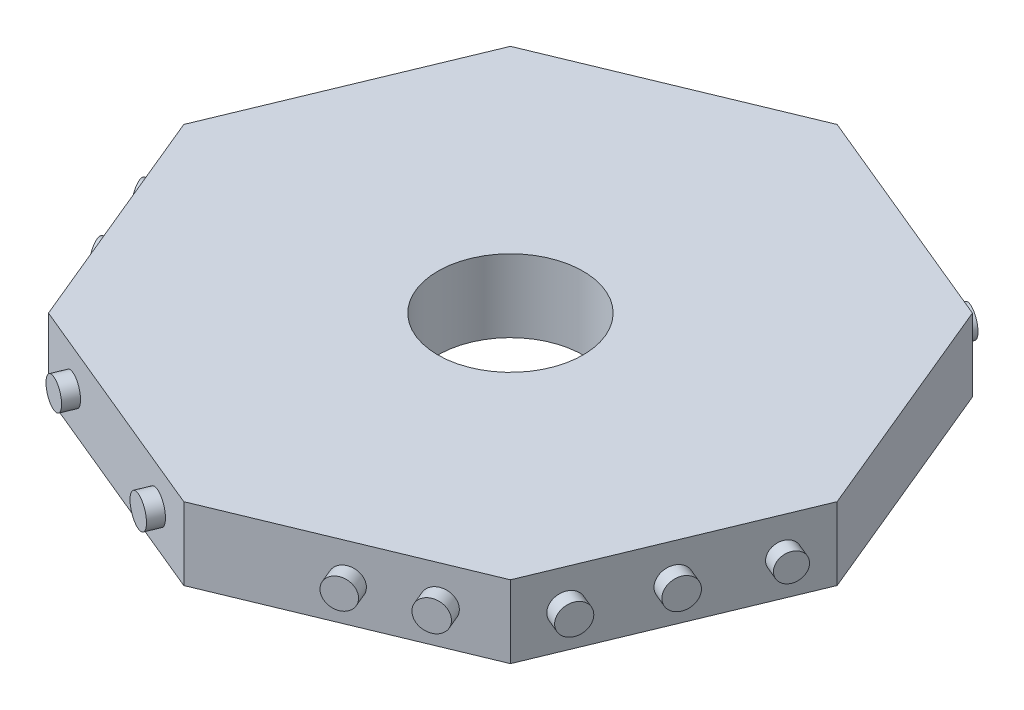
SolidWorks part; units mm, degrees
ref_plane "Front Plane" through (0, 0, 0) normal (0, 0, 1) x (1, 0, 0)
ref_plane "Top Plane" through (0, 0, 0) normal (0, 1, 0) x (1, 0, 0)
ref_plane "Right Plane" through (0, 0, 0) normal (1, 0, 0) x (0, 0, -1)
sketch "Sketch2" plane through (0, 0, 0) normal (0, 1, 0) x (1, 0, 0)
  line L1 (57.1139, 0) -> (40.3856, 40.3856)
  line L2 (40.3856, 40.3856) -> (0, 57.1139)
  line L3 (0, 57.1139) -> (-40.3856, 40.3856)
  line L4 (-40.3856, 40.3856) -> (-57.1139, 0)
  line L5 (-57.1139, 0) -> (-40.3856, -40.3856)
  line L6 (-40.3856, -40.3856) -> (0, -57.1139)
  line L7 (0, -57.1139) -> (40.3856, -40.3856)
  line L8 (40.3856, -40.3856) -> (57.1139, 0)
  circle A0 centre (0, 0) radius 52.7663 construction
extrude "Boss-Extrude1" add sketch "Sketch2" along normal blind 12.7
sketch "Sketch6" plane through (20.1928, 0, 48.7497) normal (0.3827, 0, 0.9239) x (0.9239, 0, -0.3827)
  circle A0 centre (0, 6.35) radius 2.5823
extrude "Boss-Extrude5" add sketch "Sketch6" along normal blind 2.54
sketch "Sketch8" plane through (20.1928, 0, 48.7497) normal (0.3827, 0, 0.9239) x (0.9239, 0, -0.3827)
  circle A0 centre (12.3695, 6.35) radius 2.6506
extrude "Boss-Extrude7" add sketch "Sketch8" along normal blind 2.54
sketch "Sketch9" plane through (-20.1928, 0, 48.7497) normal (-0.3827, 0, 0.9239) x (0.9239, 0, 0.3827)
  circle A0 centre (13.2827, 6.35) radius 2.6552
extrude "Boss-Extrude8" add sketch "Sketch9" along normal blind 2.54
sketch "Sketch10" plane through (-20.1928, 0, 48.7497) normal (-0.3827, 0, 0.9239) x (0.9239, 0, 0.3827)
  circle A0 centre (-14.0089, 6.35) radius 2.5136
extrude "Boss-Extrude9" add sketch "Sketch10" against normal blind 2.032 and the other way blind 2.54
sketch "Sketch11" plane through (-48.7497, 0, 20.1928) normal (-0.9239, 0, 0.3827) x (0.3827, 0, 0.9239)
  circle A0 centre (-13.6371, 6.35) radius 2.5862
extrude "Boss-Extrude10" add sketch "Sketch11" along normal blind 2.54
sketch "Sketch12" plane through (-48.7497, 0, 20.1928) normal (-0.9239, 0, 0.3827) x (0.3827, 0, 0.9239)
  circle A0 centre (0, 6.35) radius 2.6354
extrude "Boss-Extrude11" add sketch "Sketch12" along normal blind 2.54
sketch "Sketch13" plane through (-48.7497, 0, -20.1928) normal (-0.9239, 0, -0.3827) x (-0.3827, 0, 0.9239)
  circle A0 centre (14.3543, 6.35) radius 2.6101
extrude "Boss-Extrude12" add sketch "Sketch13" along normal blind 2.54
sketch "Sketch14" plane through (-20.1928, 0, -48.7497) normal (-0.3827, 0, -0.9239) x (-0.9239, 0, 0.3827)
  circle A0 centre (0, 6.35) radius 2.6353
extrude "Boss-Extrude13" add sketch "Sketch14" along normal blind 2.54
sketch "Sketch15" plane through (20.1928, 0, -48.7497) normal (0.3827, 0, -0.9239) x (-0.9239, 0, -0.3827)
  circle A0 centre (-15.0214, 6.35) radius 2.4964
extrude "Boss-Extrude14" add sketch "Sketch15" along normal blind 2.54
sketch "Sketch16" plane through (48.7497, 0, 20.1928) normal (0.9239, 0, 0.3827) x (0.3827, 0, -0.9239)
  circle A0 centre (-14.3774, 6.35) radius 2.622
extrude "Boss-Extrude15" add sketch "Sketch16" along normal blind 2.54
sketch "Sketch17" plane through (48.7497, 0, 20.1928) normal (0.9239, 0, 0.3827) x (0.3827, 0, -0.9239)
  circle A0 centre (0, 6.35) radius 2.6496
extrude "Boss-Extrude16" add sketch "Sketch17" along normal blind 2.54
sketch "Sketch18" plane through (48.7497, 0, 20.1928) normal (0.9239, 0, 0.3827) x (0.3827, 0, -0.9239)
  circle A0 centre (14.6968, 6.35) radius 2.4177
extrude "Boss-Extrude17" add sketch "Sketch18" along normal blind 2.54
sketch "Sketch25" plane through (0, 12.7, 0) normal (0, 1, 0) x (1, 0, 0)
  circle A0 centre (0, 0) radius 12.6968
extrude "Cut-Extrude1" cut sketch "Sketch25" against normal blind 12.954
